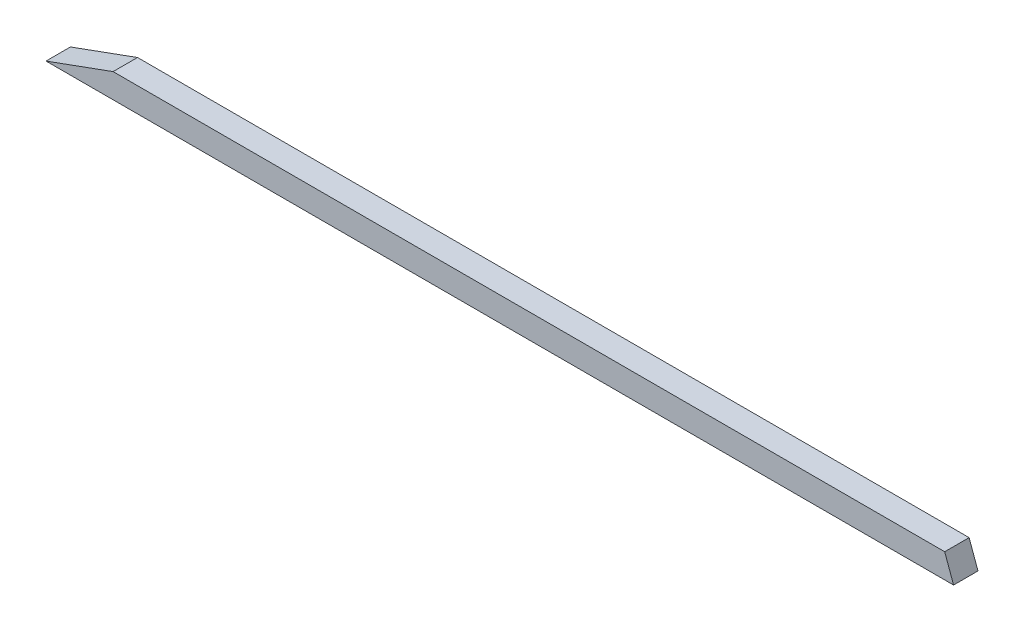
SolidWorks part; units mm, degrees
ref_plane "Front Plane" through (0, 0, 0) normal (0, 0, 1) x (1, 0, 0)
ref_plane "Top Plane" through (0, 0, 0) normal (0, 1, 0) x (1, 0, 0)
ref_plane "Right Plane" through (0, 0, 0) normal (1, 0, 0) x (0, 0, -1)
sketch "Sketch1" plane through (0, 0, 0) normal (0, 0, 1) x (1, 0, 0)
  line L1 (0, 0) -> (987.806, 0)
  line L2 (0, 0) -> (0, 20)
  line L3 (0, 20) -> (987.806, 20)
  line L4 (987.806, 0) -> (987.806, 20)
  dimension "D1" = 987.806
  dimension "D2" = 20
extrude "Boss-Extrude1" add sketch "Sketch1" along normal blind 20
sketch "Sketch2" plane through (0, 0, 20) normal (0, 0, 1) x (1, 0, 0)
  line L3 (987.806, 20) -> (0, 20) construction
  line L4 (0, 20) -> (0, 0) construction
  line L5 (0, 20) -> (0, 0)
  line L6 (0, 0) -> (54.9495, 20)
  line L7 (54.9495, 20) -> (0, 20)
  dimension "D1" = 20
extrude "Cut-Extrude1" cut sketch "Sketch2" against normal blind 20
sketch "Sketch5" plane through (0, 0, 20) normal (0, 0, 1) x (1, 0, 0)
  line L0 (987.806, 20) -> (980.5266, 0)
  line L1 (0, 0) -> (987.806, 0) construction
  line L2 (980.5266, 0) -> (987.806, 0)
  line L3 (987.806, 0) -> (987.806, 20) construction
  line L4 (987.806, 0) -> (987.806, 20)
  dimension "D1" = 20
extrude "Cut-Extrude4" cut sketch "Sketch5" against normal through all
sketch "Sketch7" plane through (0, 0, 20) normal (0, 0, 1) x (1, 0, 0)
  line L0 (743.3282, 0) -> (980.5266, 0)
  line L1 (0, 0) -> (980.5266, 0) construction
  line L2 (1312.7506, 477.8021) -> (561.6236, -152.4682) construction
  line L3 (980.5266, 0) -> (987.806, 20)
  line L4 (987.806, 20) -> (767.1632, 20)
  line L5 (987.806, 20) -> (54.9495, 20) construction
  line L6 (767.1632, 20) -> (743.3282, 0)
extrude "Cut-Extrude5" cut sketch "Sketch7" against normal through all both and the other way through all contours L6 L0 L3 L4
sketch "Sketch8" plane through (0, 0, 20) normal (0, 0, 1) x (1, 0, 0)
  line L7 (743.3282, 0) -> (736.0488, 20)
  line L8 (767.1632, 20) -> (54.9495, 20) construction
  line L9 (712.2137, 0) -> (1257.801, 457.8021) construction
  line L10 (736.0488, 20) -> (767.1632, 20)
  line L11 (767.1632, 20) -> (743.3282, 0)
extrude "Cut-Extrude9" cut sketch "Sketch8" against normal through all contours L11 L7 L10
